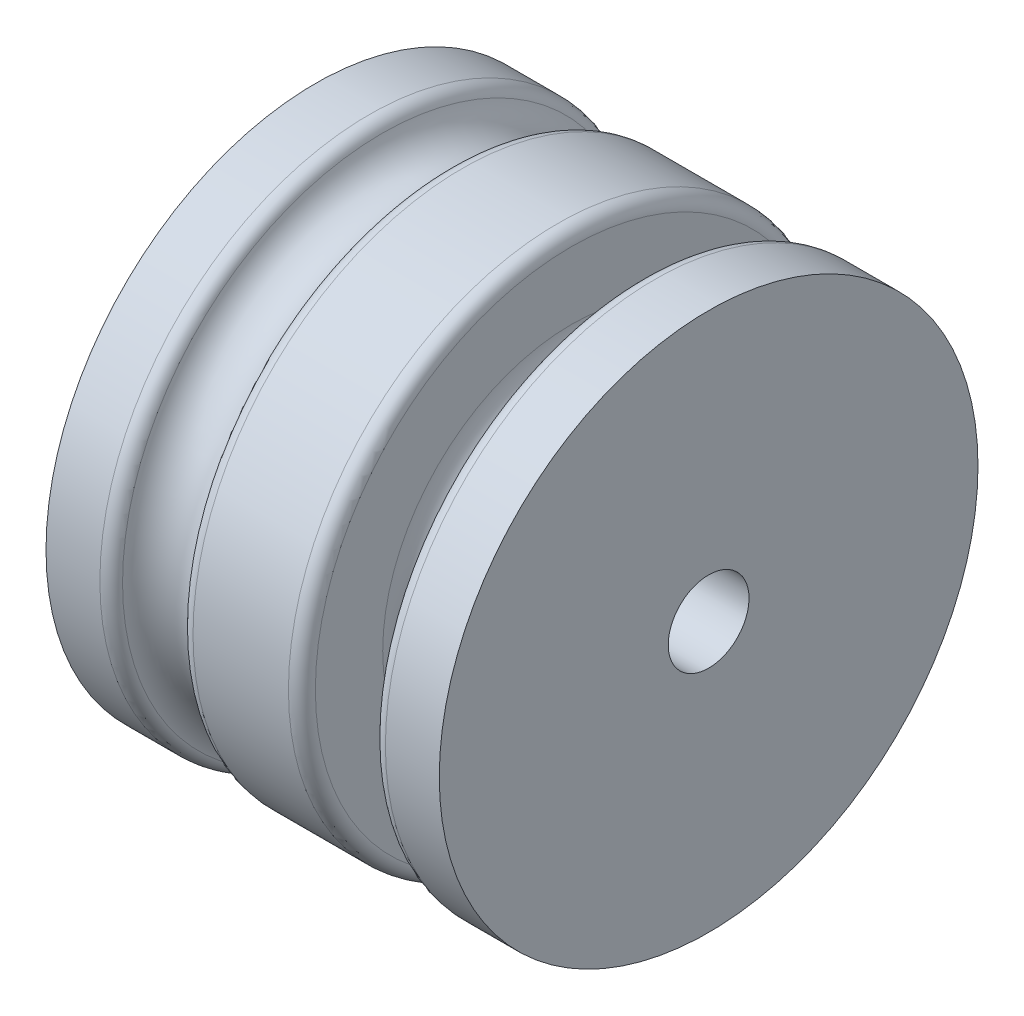
SolidWorks part; units mm, degrees
ref_plane "Front Plane" through (0, 0, 0) normal (0, 0, 1) x (1, 0, 0)
ref_plane "Top Plane" through (0, 0, 0) normal (0, 1, 0) x (1, 0, 0)
ref_plane "Right Plane" through (0, 0, 0) normal (1, 0, 0) x (0, 0, -1)
sketch "Sketch1" plane through (0, 0, 0) normal (0, 0, 1) x (1, 0, 0)
  line L0 (-14.6, 0) -> (0, 0)
  line L1 (-14.6, 0) -> (-14.6, 10)
  line L2 (-14.6, 10) -> (-12.6, 10)
  line L3 (-9.1417, 10) -> (-7.6, 10)
  line L5 (-7.6, 10) -> (-5.6, 10)
  line L6 (-5.1, 9.5) -> (-5.1, 7)
  line L7 (-2.5, 7) -> (-2.5, 9.5)
  line L8 (-2, 10) -> (0, 10)
  line L9 (0, 10) -> (0, 0)
  line L10 (-7.6, 10) -> (-7.6, 0)
  line L11 (-7.6, 15.3083) -> (-7.6, -3.5696) construction
  line L12 (-7.6, 0) -> (0, 0) construction
  arc A0 (-12.1197, 9.6389) -> (-9.622, 9.6389) centre (-10.8708, 10) ccw
  arc A1 (-5.1, 7) -> (-2.5, 7) centre (-3.8, 7) ccw
  arc A2 (-2.5, 9.5) -> (-2, 10) centre (-2, 9.5) cw
  arc A3 (-5.6, 10) -> (-5.1, 9.5) centre (-5.6, 9.5) cw
  arc A4 (-12.6, 10) -> (-12.1197, 9.6389) centre (-12.6, 9.5) cw
  arc A5 (-9.622, 9.6389) -> (-9.1417, 10) centre (-9.1417, 9.5) cw
  point P2 (0, 0)
  dimension "D1" = 1.3
  dimension "D2" = 0.5
  dimension "D5" = 2
  dimension "D6" = 7
  dimension "D3" = 1.5417
  dimension "D4" = 10
revolve "Revolve2" add sketch "Sketch1" angle 360 about L12
sketch "Sketch4" plane through (0, 0, 0) normal (1, 0, 0) x (0, 0, -1)
  circle A0 centre (0, 0) radius 1.5
  dimension "D1" = 3
extrude "Cut-Extrude1" cut sketch "Sketch4" against normal blind 20
